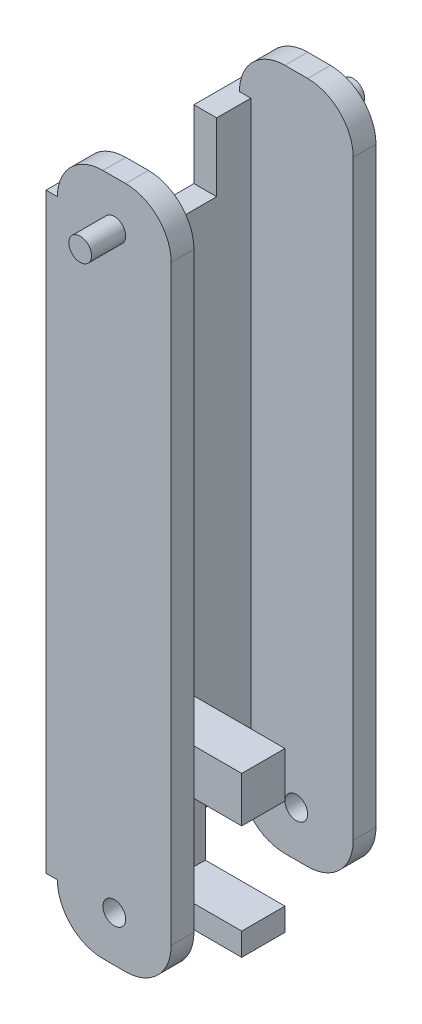
SolidWorks part; units mm, degrees
ref_plane "Front Plane" through (0, 0, 0) normal (0, 0, 1) x (1, 0, 0)
ref_plane "Top Plane" through (0, 0, 0) normal (0, 1, 0) x (1, 0, 0)
ref_plane "Right Plane" through (0, 0, 0) normal (1, 0, 0) x (0, 0, -1)
sketch "Sketch1" plane through (0, 0, 0) normal (0, 0, 1) x (1, 0, 0)
  line L0 (0, 7.8092) -> (0, -7.5836) construction
  line L1 (-16.5434, 0) -> (17.7066, 0) construction
  line L2 (-5, -20) -> (5, -20)
  line L6 (0, 7.8092) -> (0, 18.1168) construction
  line L7 (-25, 0) -> (-25, 260)
  line L8 (-5, 280) -> (5, 280)
  line L9 (25, 260) -> (25, 0)
  line L10 (0, 332.7621) -> (0, -24.8778) construction
  arc A0 (5, -20) -> (25, 0) centre (5, 0) ccw
  arc A1 (-5, -20) -> (-25, 0) centre (-5, 0) cw
  circle A2 centre (0, 0) radius 5
  arc A3 (5, 280) -> (25, 260) centre (5, 260) cw
  arc A4 (-25, 260) -> (-5, 280) centre (-5, 260) cw
  point P14 (25, -20)
  point P17 (-25, -20)
  point P22 (25, 280)
  dimension "D4" = 20
  dimension "D5" = 20
  dimension "D6" = 20
  dimension "D1" = 50
  dimension "D2" = 25
  dimension "D3" = 300
extrude "Boss-Extrude1" add sketch "Sketch1" along normal blind 10
sketch "Sketch2" plane through (0, 0, 10) normal (0, 0, 1) x (1, 0, 0)
  line L0 (0, 310.2932) -> (0, -54.3198) construction
  line L1 (5, 280) -> (-5, 280) construction
  circle A1 centre (0, 260) radius 5
  dimension "D1" = 20
  dimension "D2" = 10
extrude "Boss-Extrude2" add sketch "Sketch2" along normal blind 15
sketch "Sketch3" plane through (0, 0, 0) normal (0, 0, -1) x (-1, 0, 0)
  line L0 (0, -108.7365) -> (0, 392.6868) construction
  line L1 (25, 0) -> (20, 0)
  line L2 (20, 0) -> (20, 260)
  line L3 (20, 260) -> (25, 260)
  line L4 (25, 260) -> (25, 0)
  dimension "D1" = 260
  dimension "D2" = 260
  dimension "D3" = 5
  dimension "D4" = 20
extrude "Boss-Extrude3" add sketch "Sketch3" along normal blind 35
mirror "Mirror1" about plane through (0, 0, -35) normal (0, 0, 1) of "Boss-Extrude3", "Boss-Extrude2", "Boss-Extrude1"
sketch "Sketch8" plane through (0, 0, 0) normal (0, -1, 0) x (1, 0, 0)
  line L0 (-25, -21) -> (-20, -21)
  line L2 (-25, -70) -> (-25, 0) construction
  line L3 (-20, -70) -> (-20, 0) construction
  line L4 (-20, -21) -> (-20, -40)
  line L5 (-20, -40) -> (-25, -40)
  line L6 (-25, -40) -> (-25, -21)
  line L7 (-20, 0) -> (-25, 0) construction
  line L8 (-5, -70) -> (-25, -70) construction
  dimension "D1" = 21
  dimension "D2" = 19
  dimension "D3" = 30
extrude "Boss-Extrude4" add sketch "Sketch8" along normal blind 20
sketch "Sketch9" plane through (-20, 0, 0) normal (1, 0, 0) x (0, 0, -1)
  line L0 (21, -20) -> (21, -10)
  line L1 (21, -20) -> (21, 0) construction
  line L2 (21, -10) -> (40, -10)
  line L3 (40, -20) -> (40, 0) construction
  line L4 (40, -10) -> (40, -20)
  line L5 (40, -20) -> (21, -20)
  line L6 (21, 286.5383) -> (21, -36.1632) construction
  line L7 (40, 286.5383) -> (40, -36.1632) construction
  line L8 (40, 30) -> (21, 30)
  line L9 (21, 30) -> (21, 50)
  line L10 (21, 50) -> (40, 50)
  line L11 (40, 50) -> (40, 30)
  dimension "D1" = 10
  dimension "D2" = 40
  dimension "D3" = 20
extrude "Boss-Extrude5" add sketch "Sketch9" along normal blind 45
sketch "Sketch10" plane through (-20, 0, 0) normal (1, 0, 0) x (0, 0, -1)
  line L0 (21, 30) -> (21, -10)
  line L1 (21, -10) -> (40, -10)
  line L2 (40, -10) -> (40, 30)
  line L3 (40, 30) -> (21, 30)
extrude "Boss-Extrude6" add sketch "Sketch10" along normal blind 10
sketch "Sketch12" plane through (-25, 0, 0) normal (-1, 0, 0) x (0, 0, 1)
  line L0 (-80, 260) -> (10, 260)
  line L1 (10, 255) -> (10, 265) construction
  line L2 (10, 260) -> (10, 0)
  line L3 (10, 0) -> (-21, 0)
  line L4 (-21, 0) -> (-21, -20)
  line L5 (-21, -20) -> (-40, -20)
  line L6 (-40, -20) -> (-40, 0)
  line L7 (-80, 260) -> (-80, 0)
  line L8 (-80, 0) -> (-40, 0)
extrude "Boss-Extrude7" add sketch "Sketch12" along normal blind 5
sketch "Sketch13" plane through (-30, 0, 0) normal (-1, 0, 0) x (0, 0, 1)
  line L0 (-55, 260) -> (-55, 230)
  line L1 (10, 260) -> (-80, 260) construction
  line L2 (-55, 230) -> (-15, 230)
  line L3 (-15, 230) -> (-15, 260)
  line L4 (-15, 260) -> (-55, 260)
  line L5 (-80, 260) -> (-80, 0) construction
  line L6 (10, 0) -> (10, 260) construction
  dimension "D1" = 25
  dimension "D2" = 25
  dimension "D3" = 30
extrude "Cut-Extrude1" cut sketch "Sketch13" against normal blind 10
